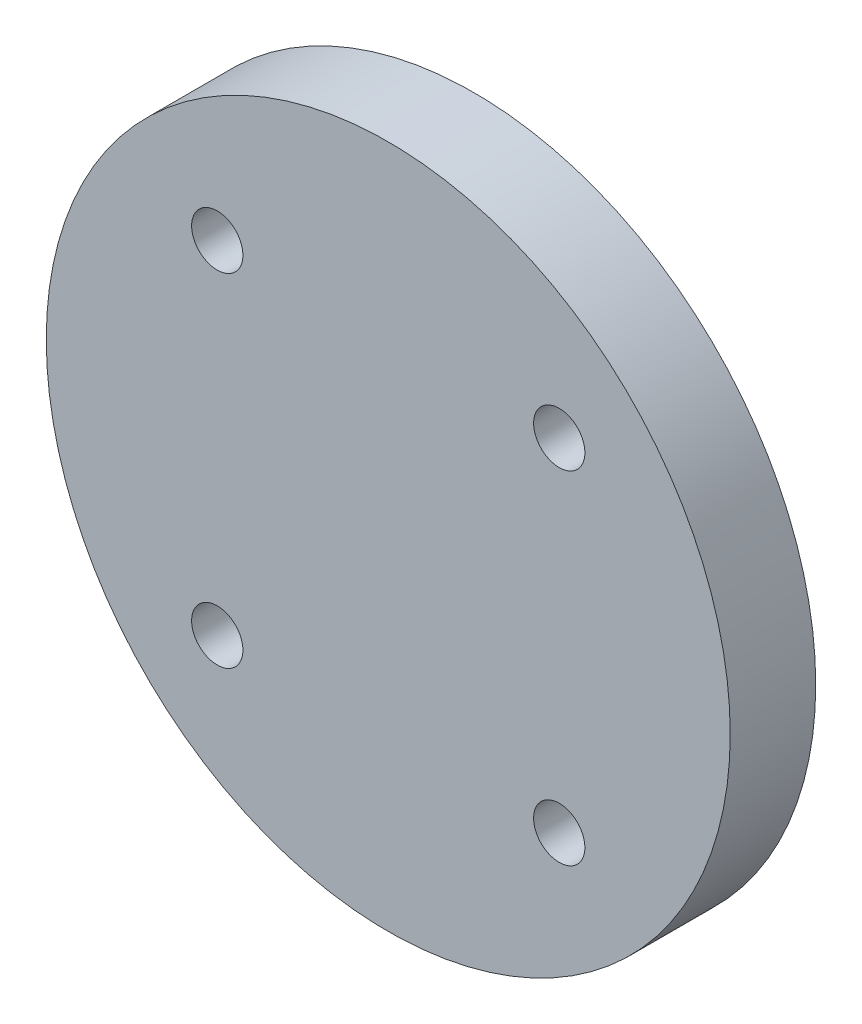
SolidWorks part; units mm, degrees
ref_plane "前基準面" through (0, 0, 0) normal (0, 0, 1) x (1, 0, 0)
ref_plane "上基準面" through (0, 0, 0) normal (0, 1, 0) x (1, 0, 0)
ref_plane "右基準面" through (0, 0, 0) normal (1, 0, 0) x (0, 0, -1)
sketch "草圖1" plane through (0, 0, 0) normal (0, 0, 1) x (1, 0, 0)
  line L0 (0, 31.7365) -> (0, -50.5627) construction
  line L1 (-43.8321, 0) -> (61.2813, 0) construction
  circle A0 centre (0, 0) radius 20
  circle A2 centre (-10, -10) radius 1.5
  circle A3 centre (-10, 10) radius 1.5
  circle A4 centre (10, 10) radius 1.5
  circle A5 centre (10, -10) radius 1.5
  dimension "D2" = 40
  dimension "D5" = 3
  dimension "D3" = 10
  dimension "D4" = 10
extrude "填料-伸長1" add sketch "草圖1" along normal blind 5
